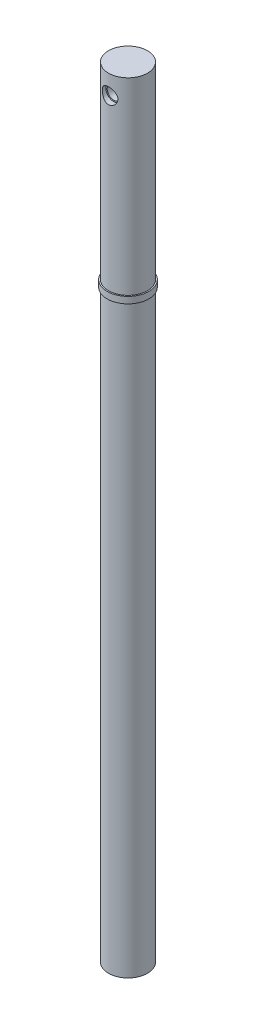
SolidWorks part; units mm, degrees
ref_plane "Front Plane" through (0, 0, 0) normal (0, 0, 1) x (1, 0, 0)
ref_plane "Top Plane" through (0, 0, 0) normal (0, 1, 0) x (1, 0, 0)
ref_plane "Right Plane" through (0, 0, 0) normal (1, 0, 0) x (0, 0, -1)
sketch "Sketch2" plane through (0, 0, 0) normal (0, 1, 0) x (1, 0, 0)
  circle A0 centre (0, 0) radius 1.5
  dimension "D1" = 3
sketch "Sketch3" plane through (0, 0, 0) normal (1, 0, 0) x (0, 0, -1)
  line L0 (0, 0) -> (0, -60)
  line L1 (1.5, 0) -> (-1.5, 0) construction
  dimension "D1" = 60
sweep "Sweep1" add profiles "Sketch2" path "Sketch3"
sketch "Sketch4" plane through (0, 0, 0) normal (0, 0, 1) x (1, 0, 0)
  circle A0 centre (0, -1.5) radius 0.5
  point P2 (0, 0)
  dimension "D1" = 1
  dimension "D2" = 1.5
extrude "Cut-Extrude1" cut sketch "Sketch4" against normal mid plane 4
sketch "Sketch6" plane through (0, 0, 0) normal (0, 0, 1) x (1, 0, 0)
  circle A2 centre (0, -1.5) radius 0.6
  circle A3 centre (0, -1.5) radius 0.6
  dimension "D1" = 0.1
extrude "Cut-Extrude2" cut sketch "Sketch6" against normal blind 0.5 from offset 1.6
sketch "Sketch7" plane through (0, 0, 0) normal (0, 1, 0) x (1, 0, 0)
  circle A2 centre (0, 0) radius 1.6
  circle A3 centre (0, 0) radius 1.6
  dimension "D1" = 0.1
extrude "Boss-Extrude1" add sketch "Sketch7" along normal blind 0.5 from offset 15
